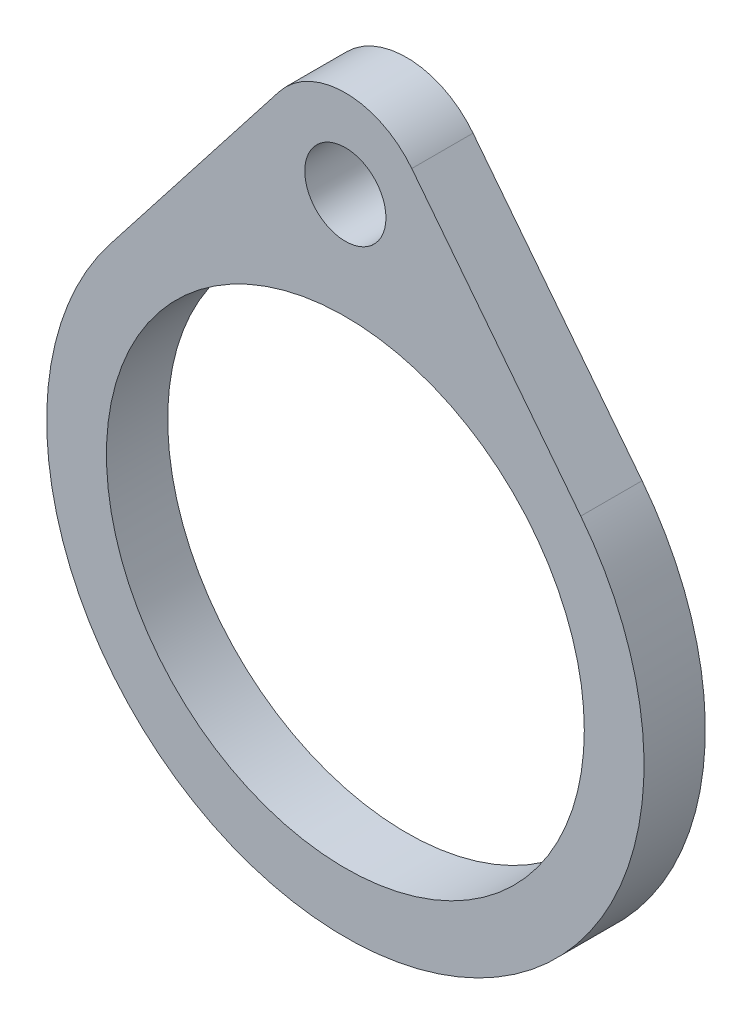
SolidWorks part; units mm, degrees
ref_plane "Front Plane" through (0, 0, 0) normal (0, 0, 1) x (1, 0, 0)
ref_plane "Top Plane" through (0, 0, 0) normal (0, 1, 0) x (1, 0, 0)
ref_plane "Right Plane" through (0, 0, 0) normal (1, 0, 0) x (0, 0, -1)
sketch "Sketch1" plane through (0, 0, 0) normal (0, 0, 1) x (1, 0, 0)
  circle A0 centre (0, 0) radius 15.6
  circle A1 centre (0, 0) radius 19.5
  dimension "D1" = 39
  dimension "D2" = 31.2
extrude "Boss-Extrude1" add sketch "Sketch1" along normal blind 4
sketch "Sketch3" plane through (0, 0, 0) normal (0, 0, 1) x (1, 0, 0)
  line L0 (-999.8994, 12) -> (49000.1006, 12) construction
  line L1 (15.3704, 12) -> (4.3352, 26.1346)
  line L2 (-15.3704, 12) -> (-4.3352, 26.1346)
  line L3 (-1000.9184, 27.9) -> (48999.0816, 27.9) construction
  circle A0 centre (0, 0) radius 19.5 construction
  circle A3 centre (0, 0) radius 15.6 construction
  circle A4 centre (0, 22.5) radius 2.65
  arc A5 (4.3352, 26.1346) -> (-4.3352, 26.1346) centre (0, 22.75) ccw
  arc A6 (-15.3704, 12) -> (15.3704, 12) centre (0, 0) cw
  dimension "D3" = 5.3
  dimension "D5" = 5.5
  dimension "D1" = 12
  dimension "D2" = 12.3
  dimension "D4" = 22.5
extrude "Boss-Extrude2" add sketch "Sketch3" along normal blind 4 contours L2 A6 L1 A5 A4
